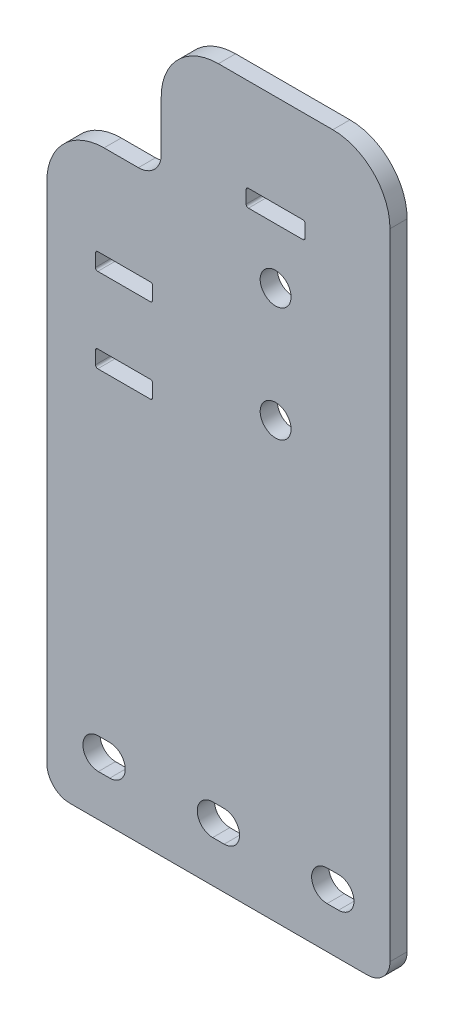
SolidWorks part; units mm, degrees
ref_plane "Ebene vorne" through (0, 0, 0) normal (0, 0, 1) x (1, 0, 0)
ref_plane "Ebene oben" through (0, 0, 0) normal (0, 1, 0) x (1, 0, 0)
ref_plane "Ebene rechts" through (0, 0, 0) normal (1, 0, 0) x (0, 0, -1)
sketch "Model" plane through (0, 0, 0) normal (0, 0, 1) x (1, 0, 0)
  line L0 (16, 102.25) -> (10, 102.25)
  line L1 (0, 92.25) -> (0, 4)
  line L2 (4, 0) -> (56, 0)
  line L3 (60, 4) -> (60, 115)
  line L4 (50, 125) -> (30, 125)
  line L5 (20, 115) -> (20, 106.25)
  line L6 (11, 7.3) -> (9, 7.3)
  line L7 (9, 12.7) -> (11, 12.7)
  line L8 (31, 7.3) -> (29, 7.3)
  line L9 (29, 12.7) -> (31, 12.7)
  line L10 (51, 7.3) -> (49, 7.3)
  line L11 (49, 12.7) -> (51, 12.7)
  line L12 (18.1, 83) -> (8.9, 83)
  line L13 (8.5, 83.4) -> (8.5, 85.6)
  line L14 (8.9, 86) -> (18.1, 86)
  line L15 (18.5, 85.6) -> (18.5, 83.4)
  line L16 (18.1, 68.25) -> (8.9, 68.25)
  line L17 (8.5, 68.65) -> (8.5, 70.85)
  line L18 (8.9, 71.25) -> (18.1, 71.25)
  line L19 (18.5, 70.85) -> (18.5, 68.65)
  line L20 (44.75, 105.75) -> (35.25, 105.75)
  line L21 (34.85, 106.15) -> (34.85, 108.35)
  line L22 (35.25, 108.75) -> (44.75, 108.75)
  line L23 (45.15, 108.35) -> (45.15, 106.15)
  circle A0 centre (40, 76) radius 2.7
  circle A1 centre (40, 96) radius 2.7
  arc A2 (10, 102.25) -> (0, 92.25) centre (10, 92.25) ccw
  arc A3 (0, 4) -> (4, 0) centre (4, 4) ccw
  arc A4 (56, 0) -> (60, 4) centre (56, 4) ccw
  arc A5 (60, 115) -> (50, 125) centre (50, 115) ccw
  arc A6 (30, 125) -> (20, 115) centre (30, 115) ccw
  arc A7 (16, 102.25) -> (20, 106.25) centre (16, 106.25) ccw
  arc A8 (9, 12.7) -> (9, 7.3) centre (9, 10) ccw
  arc A9 (11, 7.3) -> (11, 12.7) centre (11, 10) ccw
  arc A10 (29, 12.7) -> (29, 7.3) centre (29, 10) ccw
  arc A11 (31, 7.3) -> (31, 12.7) centre (31, 10) ccw
  arc A12 (49, 12.7) -> (49, 7.3) centre (49, 10) ccw
  arc A13 (51, 7.3) -> (51, 12.7) centre (51, 10) ccw
  arc A14 (8.5, 83.4) -> (8.9, 83) centre (8.9, 83.4) ccw
  arc A15 (8.9, 86) -> (8.5, 85.6) centre (8.9, 85.6) ccw
  arc A16 (18.5, 85.6) -> (18.1, 86) centre (18.1, 85.6) ccw
  arc A17 (18.1, 83) -> (18.5, 83.4) centre (18.1, 83.4) ccw
  arc A18 (8.5, 68.65) -> (8.9, 68.25) centre (8.9, 68.65) ccw
  arc A19 (8.9, 71.25) -> (8.5, 70.85) centre (8.9, 70.85) ccw
  arc A20 (18.5, 70.85) -> (18.1, 71.25) centre (18.1, 70.85) ccw
  arc A21 (18.1, 68.25) -> (18.5, 68.65) centre (18.1, 68.65) ccw
  arc A22 (34.85, 106.15) -> (35.25, 105.75) centre (35.25, 106.15) ccw
  arc A23 (35.25, 108.75) -> (34.85, 108.35) centre (35.25, 108.35) ccw
  arc A24 (45.15, 108.35) -> (44.75, 108.75) centre (44.75, 108.35) ccw
  arc A25 (44.75, 105.75) -> (45.15, 106.15) centre (44.75, 106.15) ccw
extrude "Aufsatz-Linear austragen1" add sketch "Model" along normal blind 3
